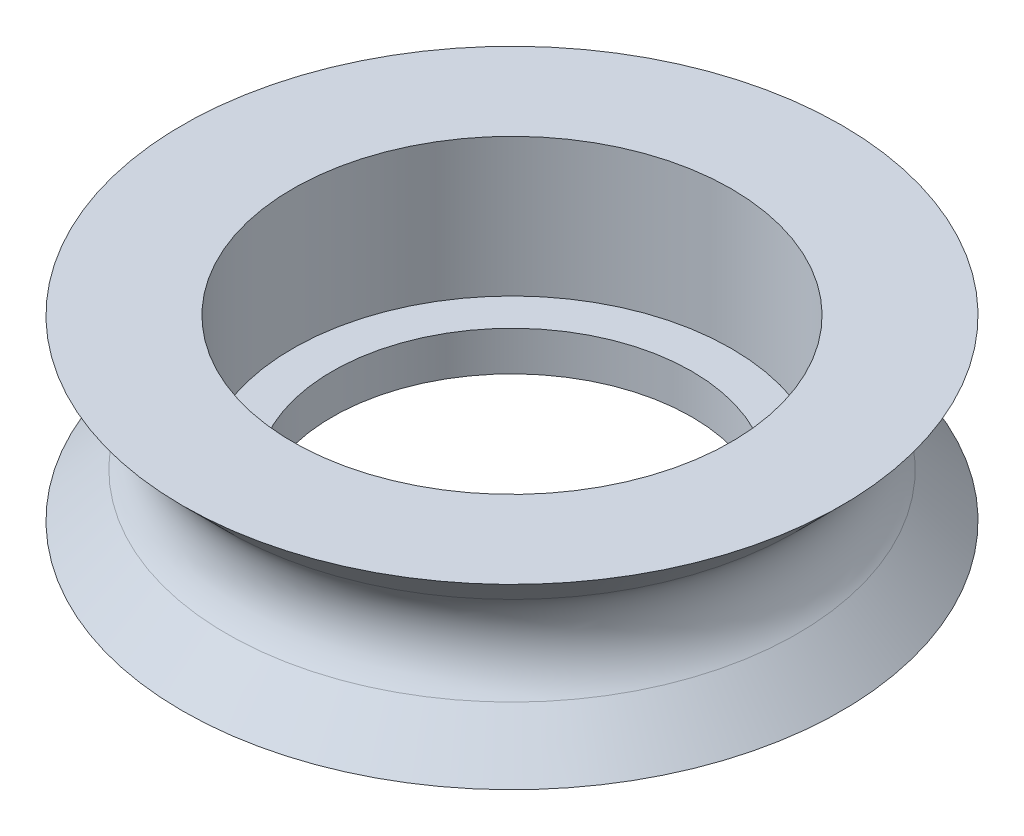
SolidWorks part; units mm, degrees
ref_plane "Front Plane" through (0, 0, 0) normal (0, 0, 1) x (1, 0, 0)
ref_plane "Top Plane" through (0, 0, 0) normal (0, 1, 0) x (1, 0, 0)
ref_plane "Right Plane" through (0, 0, 0) normal (1, 0, 0) x (0, 0, -1)
sketch "Sketch1" plane through (0, 0, 0) normal (0, 0, 1) x (1, 0, 0)
  line L0 (0, 0) -> (0, 55.8251) construction
  line L1 (11.1, 0) -> (11.1, 7)
  line L2 (11.1, 7) -> (16.682, 7)
  line L3 (11.1, 0) -> (9.1, 0)
  line L4 (9.1, 0) -> (9.1, -2)
  line L5 (9.1, -2) -> (16.682, -2)
  line L6 (16.682, 7) -> (16.682, -2) construction
  line L7 (16.682, 7) -> (14.432, 4.75)
  line L8 (14.432, 0.25) -> (16.682, -2)
  arc A0 (14.432, 4.75) -> (14.432, 0.25) centre (16.682, 2.5) ccw
  circle A1 centre (15.0875, 2.5) radius 1.5875 construction
  dimension "D1" = 22.2
  dimension "D3" = 2
  dimension "D5" = 45
  dimension "D8" = 3.175
  dimension "D9" = 2.4
  dimension "D2" = 7
  dimension "D4" = 2
  dimension "D6" = 33.364
  dimension "D7" = 225
  dimension "D10" = 15.0875
revolve "Revolve1" add sketch "Sketch1" angle 360 about L0
